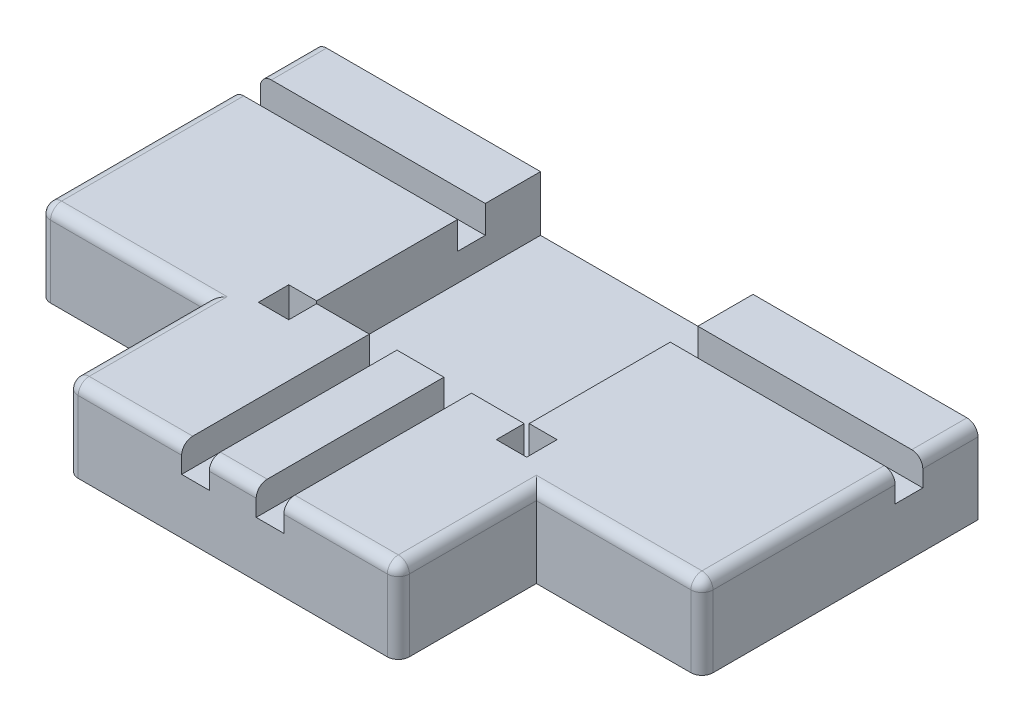
SolidWorks part; units mm, degrees
ref_plane "Front Plane" through (0, 0, 0) normal (0, 0, 1) x (1, 0, 0)
ref_plane "Top Plane" through (0, 0, 0) normal (0, 1, 0) x (1, 0, 0)
ref_plane "Right Plane" through (0, 0, 0) normal (1, 0, 0) x (0, 0, -1)
sketch "Sketch1" plane through (0, 0, 0) normal (0, 1, 0) x (1, 0, 0)
  line L1 (-60, -50) -> (60, -50)
  line L2 (-60, -50) -> (-60, 50)
  line L3 (-60, 50) -> (60, 50)
  line L4 (60, -50) -> (60, 50)
  line L5 (-60, -50) -> (60, 50) construction
  line L6 (-60, 50) -> (60, -50) construction
  point P0 (0, 0)
  dimension "D1" = 120
  dimension "D2" = 100
extrude "Boss-Extrude1" add sketch "Sketch1" along normal blind 15
sketch "Sketch2" plane through (0, 15, 0) normal (0, 1, 0) x (1, 0, 0)
  line L1 (-19.25, -41) -> (19.25, -41)
  line L2 (-19.25, -41) -> (-19.25, 41)
  line L3 (-19.25, 41) -> (19.25, 41)
  line L4 (19.25, -41) -> (19.25, 41)
  line L5 (-19.25, -41) -> (19.25, 41) construction
  line L6 (-19.25, 41) -> (19.25, -41) construction
  point P0 (0, 0)
  dimension "D1" = 82
  dimension "D2" = 38.5
sketch "Sketch7" plane through (0, 0, 0) normal (0, 1, 0) x (1, 0, 0)
  line L0 (0, 50) -> (0, 75) construction
  line L1 (60, 50) -> (-60, 50) construction
  line L2 (-60, -50) -> (60, -50) construction
  line L3 (0, -50) -> (0, -75) construction
  line L5 (-30, 50) -> (30, 50)
  line L6 (-30, 50) -> (-30, 75)
  line L7 (-30, 75) -> (30, 75)
  line L8 (30, 50) -> (30, 75)
  line L9 (-30, 50) -> (30, 75) construction
  line L10 (-30, 75) -> (30, 50) construction
  line L11 (-30, -75) -> (30, -75)
  line L12 (-30, -75) -> (-30, -50)
  line L13 (-30, -50) -> (30, -50)
  line L14 (30, -75) -> (30, -50)
  line L15 (-30, -75) -> (30, -50) construction
  line L16 (-30, -50) -> (30, -75) construction
  point P7 (0, 62.5)
  point P15 (0, -62.5)
  dimension "D1" = 25
  dimension "D2" = 25
  dimension "D3" = 60
  dimension "D4" = 60
extrude "Boss-Extrude6" add sketch "Sketch7" along normal blind 15 contours L11 L14 L13 L12 | L5 L8 L7 L6
fillet "Fillet1" radius 2 20 edges at (60, 7.5, -50) (60, 7.5, 50) (30, 7.5, -75) (30, 15, -62.5) (45, 15, -50) (0, 15, -75) (-30, 15, -62.5) (-45, 15, -50) (-45, 15, 50) (-30, 15, 62.5) (30, 15, 62.5) (45, 15, 50) (60, 15, 0) (-60, 15, 0) (0, 15, 75) (30, 7.5, 75) (-30, 7.5, 75) (-60, 7.5, 50) (-60, 7.5, -50) (-30, 7.5, -75)
sketch "Sketch10" plane through (0, 15, 0) normal (0, 1, 0) x (1, 0, 0)
  line L0 (-9.25, -40.5) -> (-9.25, -33.1629)
  line L15 (-82.8084, 15) -> (-19.25, 15)
  line L22 (-82.8084, 10) -> (-19.25, 10)
  line L24 (-9.25, -89.7663) -> (-4.25, -89.7663)
  line L27 (-4.25, -89.7663) -> (-4.25, -40.5)
  line L32 (-82.8084, 15) -> (-82.8084, 10)
  line L33 (-9.25, -40.5) -> (-9.25, -89.7663)
  line L34 (-9.25, -33.1629) -> (-4.25, -33.1629)
  line L35 (-4.25, -33.1629) -> (-4.25, -40.5)
  line L36 (-19.25, 10) -> (-11.5551, 10)
  line L37 (-11.5551, 10) -> (-11.5551, 15)
  line L38 (-11.5551, 15) -> (-19.25, 15)
  dimension "D3" = 5
  dimension "D6" = 5
extrude "Cut-Extrude1" cut sketch "Sketch2" along direction (0, -1, 0) on the side against the normal blind 10
extrude "Cut-Extrude3" cut sketch "Sketch10" against normal blind 5
sketch "Sketch11" plane through (0, 15, 0) normal (0, 1, 0) x (1, 0, 0)
  line L6 (-19.25, 41) -> (-24.2997, 46.0497) construction
  line L8 (-24.2997, 46.0497) -> (-18.7997, 46.0497)
  line L9 (-24.2997, 46.0497) -> (-24.2997, 40.5497)
  line L10 (-24.2997, 40.5497) -> (-18.7997, 40.5497)
  line L11 (-18.7997, 46.0497) -> (-18.7997, 40.5497)
  dimension "D1" = 7.1414
  dimension "D2" = 5.5
  dimension "D3" = 5.5
extrude "Cut-Extrude6" cut sketch "Sketch11" against normal blind 7
mirror "Mirror3" about plane through (0, 0, 0) normal (1, 0, 0) of "Cut-Extrude6" second plane through (0, 0, 0) second plane normal (0, 0, 1)
mirror "Mirror4" about plane through (0, 0, 0) normal (1, 0, 0) of "Cut-Extrude3" second plane through (0, 0, 0) second plane normal (0, 0, 1)
sketch "Sketch12" plane through (0, 0, 0) normal (0, 0, 1) x (1, 0, 0)
  line L1 (-66.1558, 18.9039) -> (65.6223, 18.9039)
  line L2 (-66.1558, 18.9039) -> (-66.1558, -2.8368)
  line L3 (-66.1558, -2.8368) -> (65.6223, -2.8368)
  line L4 (65.6223, 18.9039) -> (65.6223, -2.8368)
extrude "Cut-Extrude7" cut sketch "Sketch12" against normal up to next
